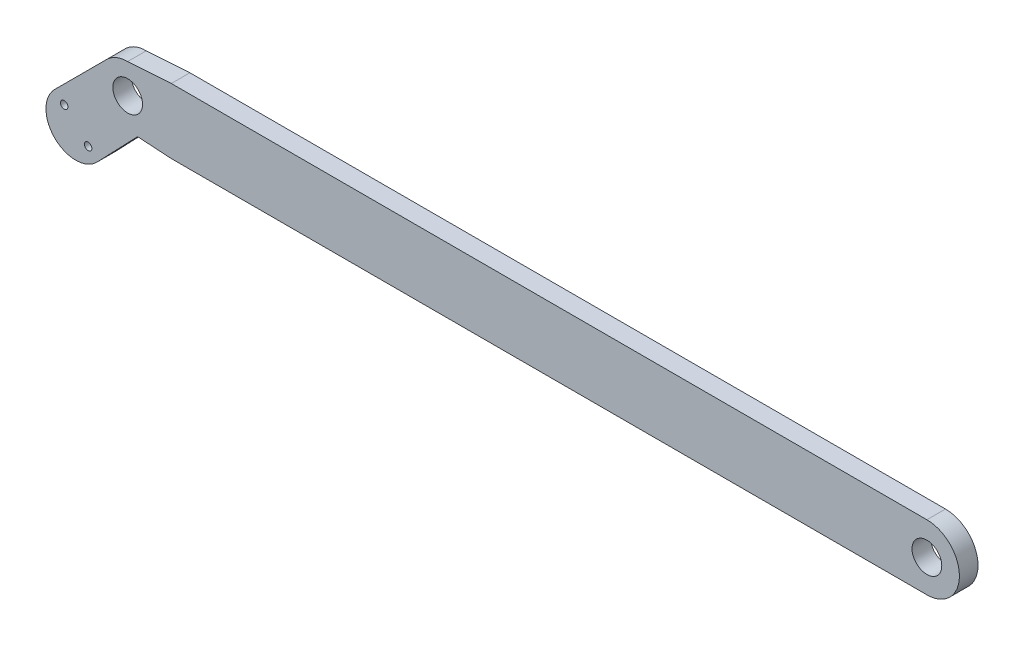
SolidWorks part; units mm, degrees
ref_plane "前视基准面" through (0, 0, 0) normal (0, 0, 1) x (1, 0, 0)
ref_plane "上视基准面" through (0, 0, 0) normal (0, 1, 0) x (1, 0, 0)
ref_plane "右视基准面" through (0, 0, 0) normal (1, 0, 0) x (0, 0, -1)
other "Configuration Table"
sketch "草图3" plane through (0, 0, 0) normal (0, 0, 1) x (1, 0, 0)
  line L0 (203.2592, 8.75) -> (0, 8.75)
  line L1 (0, -8.75) -> (215, -8.75)
  line L2 (0, 8.75) -> (-11.7408, 8)
  line L3 (0, -8.75) -> (-11.7408, -8)
  line L4 (203.2592, 8.75) -> (203.2592, -8.75)
  circle A0 centre (-11.7408, 0) radius 8
  circle A1 centre (203.2592, 0) radius 8.75
  dimension "D1" = 16
  dimension "D2" = 17.5
  dimension "D3" = 215
extrude "凸台-拉伸1" add sketch "草图3" along normal blind 5 contours A1 L0 L2 A0 L3 L1 | A0 | L4 A1 | L4 A1
sketch "草图4" plane through (0, 0, 5) normal (0, 0, 1) x (1, 0, 0)
  circle A0 centre (-11.7408, 0) radius 4
  circle A1 centre (203.2592, 0) radius 4
  dimension "D1" = 8
  dimension "D2" = 8
extrude "切除-拉伸1" cut sketch "草图4" against normal through all
sketch "草图5" plane through (0, 0, 0) normal (0, 0, 1) x (1, 0, 0)
  line L0 (-11.7408, 0) -> (-25.725, -13.9842)
  line L1 (-25.725, -13.9842) -> (-11.7408, 0)
  line L2 (-11.7408, 0) -> (0, 0)
  line L3 (-31.3819, -8.3273) -> (-17.4001, 5.6545)
  line L4 (-19.9468, -19.517) -> (-9.0817, -8.1699)
  line L5 (0, -8.75) -> (-11.7408, -8) construction
  line L6 (-11.7408, -8) -> (-9.0817, -8.1699)
  circle A0 centre (-25.725, -13.9842) radius 8
  circle A2 centre (-28.8185, -10.634) radius 1
  circle A3 centre (-22.3749, -17.0777) radius 1
  arc A4 (-11.7408, 8) -> (-11.7408, -8) centre (-11.7408, 0) ccw construction
  circle A5 centre (-11.7408, 0) radius 8
  dimension "D2" = 16
  dimension "D3" = 2
  dimension "D1" = 135
  dimension "D4" = 15.7101
extrude "凸台-拉伸3" add sketch "草图5" along normal blind 5
